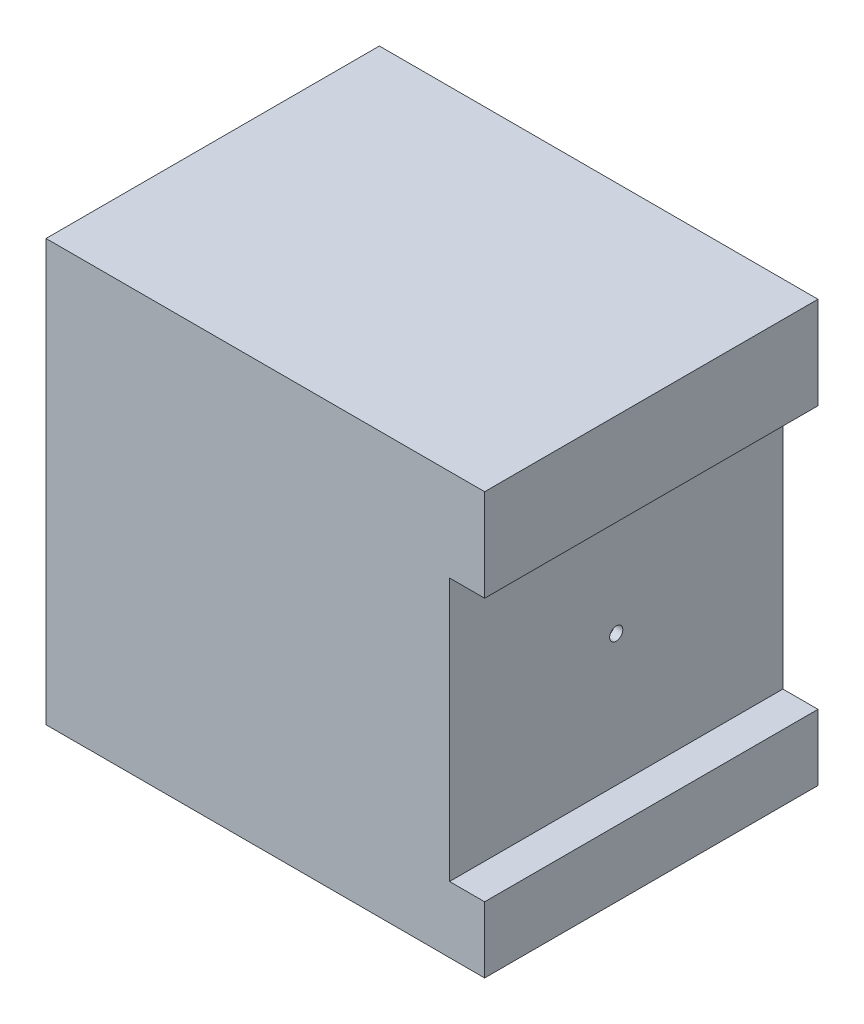
SolidWorks part; units mm, degrees
ref_plane "Front Plane" through (0, 0, 0) normal (0, 0, 1) x (1, 0, 0)
ref_plane "Top Plane" through (0, 0, 0) normal (0, 1, 0) x (1, 0, 0)
ref_plane "Right Plane" through (0, 0, 0) normal (1, 0, 0) x (0, 0, -1)
sketch "Sketch1" plane through (0, 0, 0) normal (0, 0, 1) x (1, 0, 0)
  line L1 (-25, 22.5) -> (25, 22.5)
  line L2 (-25, 22.5) -> (-25, -22.5)
  line L3 (-25, -22.5) -> (25, -22.5)
  line L4 (25, 22.5) -> (25, -22.5)
  line L5 (-25, 22.5) -> (25, -22.5) construction
  line L6 (-25, -22.5) -> (25, 22.5) construction
  point P0 (0, 0)
  dimension "D1" = 50
  dimension "D2" = 45
extrude "Boss-Extrude1" add sketch "Sketch1" along normal blind 4
sketch "Sketch2" plane through (25, 0, 0) normal (1, 0, 0) x (0, 0, -1)
  line L1 (-4, 22.5) -> (34, 22.5)
  line L2 (-4, 22.5) -> (-4, -22.5073)
  line L3 (-4, -22.5073) -> (34, -22.5073)
  line L4 (34, 22.5) -> (34, -22.5073)
  dimension "D1" = 38
extrude "Boss-Extrude2" add sketch "Sketch2" against normal blind 5
sketch "Sketch3" plane through (0, 22.5, 0) normal (0, 1, 0) x (1, 0, 0)
  line L1 (25, 34) -> (-25, 34)
  line L2 (25, 34) -> (25, -4)
  line L3 (25, -4) -> (-25, -4)
  line L4 (-25, 34) -> (-25, -4)
extrude "Boss-Extrude3" add sketch "Sketch3" along normal blind 3
sketch "Sketch4" plane through (-25, 0, 0) normal (-1, 0, 0) x (0, 0, 1)
  line L1 (4, 25.5) -> (-34, 25.5)
  line L2 (4, 25.5) -> (4, -22.5073)
  line L3 (4, -22.5073) -> (-34, -22.5073)
  line L4 (-34, 25.5) -> (-34, -22.5073)
extrude "Boss-Extrude4" add sketch "Sketch4" against normal blind 5
sketch "Sketch5" plane through (25, 0, 0) normal (1, 0, 0) x (0, 0, -1)
  line L0 (-4, -22.5073) -> (15, -22.5073) construction
  line L1 (-4, -22.5073) -> (34, -22.5073) construction
  line L2 (15, -22.5073) -> (15, 0) construction
  line L3 (34, -22.5073) -> (34, 25.5) construction
  line L4 (-4, 14.9821) -> (34, 14.9821)
  line L5 (-4, 14.9821) -> (-4, -14.9821)
  line L6 (-4, -14.9821) -> (34, -14.9821)
  line L7 (34, 14.9821) -> (34, -14.9821)
  line L8 (-4, 14.9821) -> (34, -14.9821) construction
  line L9 (-4, -14.9821) -> (34, 14.9821) construction
extrude "Cut-Extrude3" cut sketch "Sketch5" against normal blind 4
sketch "Sketch7" plane through (-25, 0, 0) normal (-1, 0, 0) x (0, 0, 1)
  line L0 (-34, -22.5073) -> (-15, -22.5073)
  line L1 (-34, -22.5073) -> (4, -22.5073) construction
  circle A0 centre (-15, 0) radius 0.75
extrude "Cut-Extrude4" cut sketch "Sketch7" against normal blind 54 contours A0
